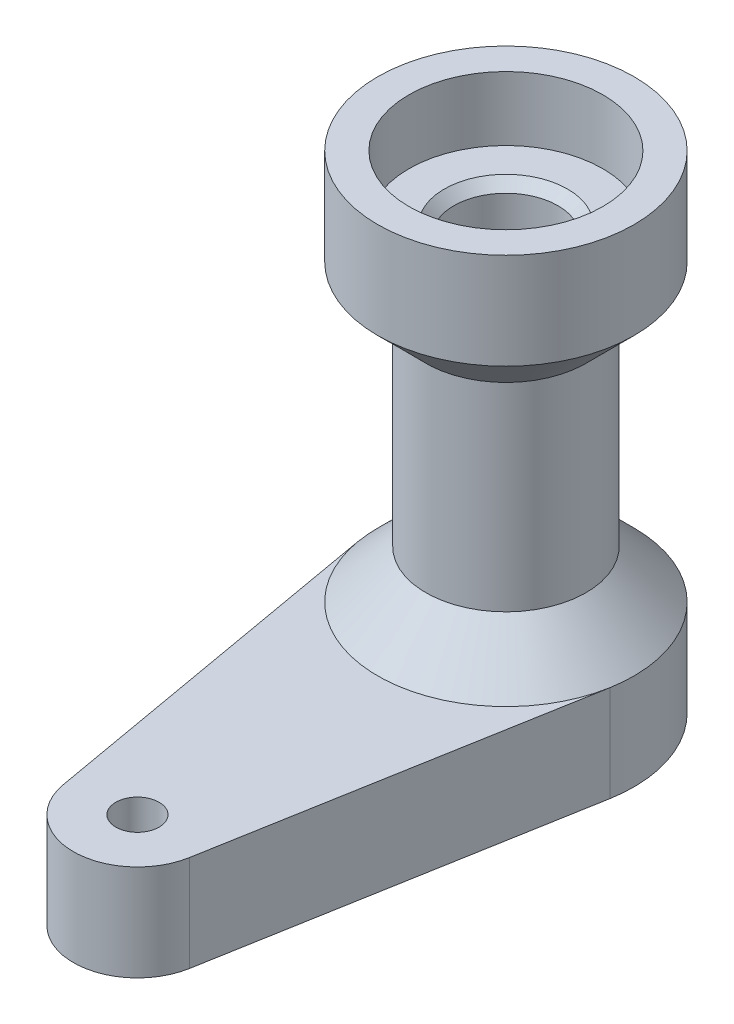
SolidWorks part; units mm, degrees
material "PET"
ref_plane "Plan de face" through (0, 0, 0) normal (0, 0, 1) x (1, 0, 0)
ref_plane "Plan de dessus" through (0, 0, 0) normal (0, 1, 0) x (1, 0, 0)
ref_plane "Plan de droite" through (0, 0, 0) normal (1, 0, 0) x (0, 0, -1)
sketch "Esquisse1" plane through (0, 0, 0) normal (0, 0, 1) x (1, 0, 0)
  line L0 (0, -1.1442) -> (0, 29.6304) construction
  line L1 (-6.05, 0) -> (-6.05, 4)
  line L2 (-6.05, 4) -> (-3.85, 4)
  line L3 (-3.25, 4.6) -> (-3.25, 25.8)
  line L4 (-3.85, 26.4) -> (-6.05, 26.4)
  line L5 (-6.05, 26.4) -> (-6.05, 30.4)
  line L6 (-6.05, 30.4) -> (-8, 30.4)
  line L7 (-8, 30.4) -> (-8, 24.4)
  line L8 (-8, 24.4) -> (-5, 21.4)
  line L9 (-5, 21.4) -> (-5, 9)
  line L10 (-5, 9) -> (-8, 6)
  line L11 (-8, 6) -> (-8, 0)
  line L12 (-8, 0) -> (-6.05, 0)
  line L13 (-3.25, 25.8) -> (-3.85, 26.4)
  line L14 (-3.85, 4) -> (-3.25, 4.6)
  point P6 (-3.25, 4)
  point P7 (-3.25, 26.4)
  dimension "D1" = 16
  dimension "D2" = 6.5
  dimension "D3" = 12.1
  dimension "D4" = 30.4
  dimension "D5" = 6
  dimension "D6" = 4
  dimension "D7" = 10
  dimension "D8" = 45
revolve "Révolution1" add sketch "Esquisse1" angle 360 about L0
sketch "Esquisse2" plane through (0, 0, 0) normal (0, 1, 0) x (1, 0, 0)
  line L0 (-7.8781, -1.3913) -> (-3.939, -23.6957)
  line L2 (3.939, -23.6957) -> (7.8781, -1.3913)
  circle A0 centre (0, -23) radius 1.35
  arc A1 (3.939, -23.6957) -> (-3.939, -23.6957) centre (0, -23) cw
  arc A6 (-7.8781, -1.3913) -> (7.8781, -1.3913) centre (0, 0) ccw
  circle A7 centre (0, 0) radius 8 construction
  dimension "D1" = 4
  dimension "D2" = 23
  dimension "D3" = 2.7
extrude "Boss.-Extru.2" add sketch "Esquisse2" along normal up to vertex (6 mm away) up to point (-8, 6, 0)
